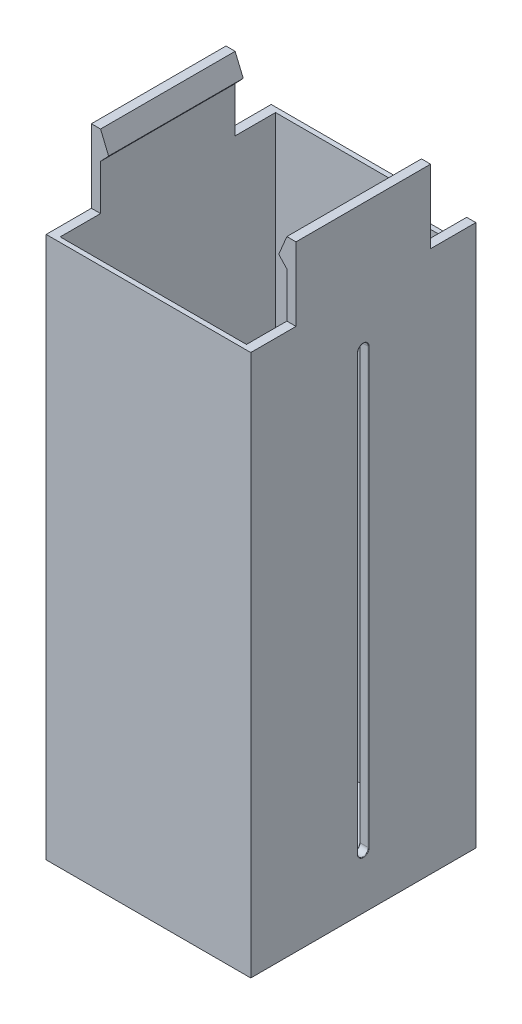
SolidWorks part; units mm, degrees
ref_plane "Front Plane" through (0, 0, 0) normal (0, 0, 1) x (1, 0, 0)
ref_plane "Top Plane" through (0, 0, 0) normal (0, 1, 0) x (1, 0, 0)
ref_plane "Right Plane" through (0, 0, 0) normal (1, 0, 0) x (0, 0, -1)
sketch "Sketch1" plane through (0, 0, 0) normal (0, 1, 0) x (1, 0, 0)
  line L0 (-19, 20.9) -> (42.3707, 20.9) construction
  line L1 (-19, 20.9) -> (19, 20.9)
  line L2 (-19, 20.9) -> (-19, -20.9)
  line L3 (-19, -20.9) -> (19, -20.9)
  line L4 (19, 20.9) -> (19, -20.9)
  line L5 (-19, 20.9) -> (19, -20.9) construction
  line L6 (-19, -20.9) -> (19, 20.9) construction
  line L7 (17.3, 20) -> (-17.3, 20)
  line L8 (17.3, 20) -> (17.3, -20)
  line L9 (17.3, -20) -> (-17.3, -20)
  line L10 (-17.3, 20) -> (-17.3, -20)
  line L11 (17.3, 20) -> (-17.3, -20) construction
  line L12 (17.3, -20) -> (-17.3, 20) construction
  point P0 (0, 0)
  point P6 (0, 0)
  dimension "D1" = 34.6
  dimension "D2" = 40
  dimension "D3" = 1.7
  dimension "D5" = 0.9
extrude "Boss-Extrude1" add sketch "Sketch1" along normal blind 100
sketch "Sketch2" plane through (0, 100, 0) normal (0, 1, 0) x (1, 0, 0)
  line L0 (-23.425, 0) -> (23.575, 0) construction
  line L1 (-19, 20.9) -> (-19, -20.9) construction
  line L3 (-17.3, 24.7662) -> (-17.3, -22.0296) construction
  line L4 (0, 23.9453) -> (0, -27.2839) construction
  line L5 (17.3, 12.5) -> (19, 12.5)
  line L6 (-17.3, -12.5) -> (-19, -12.5)
  line L7 (-17.3, -12.5) -> (-17.3, 12.5)
  line L8 (-17.3, 12.5) -> (-19, 12.5)
  line L9 (-19, -12.5) -> (-19, 12.5)
  line L10 (-17.3, -12.5) -> (-19, 12.5) construction
  line L11 (-17.3, 12.5) -> (-19, -12.5) construction
  line L12 (19, -12.5) -> (19, 12.5)
  line L13 (17.3, -12.5) -> (19, -12.5)
  line L14 (17.3, -12.5) -> (17.3, 12.5)
  line L15 (-17.3, 20) -> (-17.3, -20) construction
  point P11 (-18.15, 0)
  dimension "D2" = 25
  dimension "D3" = 20
extrude "Boss-Extrude2" add sketch "Sketch2" along normal blind 13.6
sketch "Sketch5" plane through (0, 0, 12.5) normal (0, 0, 1) x (1, 0, 0)
  line L0 (-15.8, 110) -> (15.8, 110) construction
  line L1 (17.3, 113.6) -> (17.3, 100) construction
  line L4 (-15.8, 110) -> (-17.3, 108.4)
  line L5 (-17.3, 108.4) -> (-17.3, 113.6)
  line L7 (-17.3, 113.6) -> (-15.8, 110)
  line L8 (17.3, 108.4) -> (17.3, 113.6)
  line L9 (15.8, 110) -> (17.3, 108.4)
  line L10 (17.3, 113.6) -> (15.8, 110)
  line L11 (-17.3, 113.6) -> (-17.3, 100) construction
  dimension "D1" = 10
  dimension "D2" = 1.6
  dimension "D3" = 1.5
  dimension "D4" = 1.6
  dimension "D5" = 1.5
extrude "Boss-Extrude5" add sketch "Sketch5" against normal up to surface (25 mm away) up to face at (18.15, 106.8, -12.5)
sketch "Sketch6" plane through (0, 0, 0) normal (0, -1, 0) x (1, 0, 0)
  line L0 (-19, 20.9) -> (19, 20.9) construction
  line L1 (19, 20.9) -> (-19, 20.9)
  line L2 (19, 20.9) -> (19, -20.9)
  line L3 (19, -20.9) -> (-19, -20.9)
  line L4 (-19, 20.9) -> (-19, -20.9)
extrude "Boss-Extrude6" add sketch "Sketch6" along normal blind 0.6
sketch "Sketch7" plane through (0, 0, -20.9) normal (0, 0, -1) x (-1, 0, 0)
  line L1 (-17.3, 100) -> (-4, 100)
  line L2 (-17.3, 100) -> (-17.3, 95.6)
  line L3 (-17.3, 95.6) -> (-4, 95.6)
  line L4 (-4, 100) -> (-4, 95.6)
  line L5 (-19, 100) -> (19, 100) construction
  line L6 (-19, 100) -> (-19, -0.6) construction
  dimension "D1" = 1.7
  dimension "D2" = 4.4
  dimension "D3" = 13.3
extrude "Cut-Extrude1" cut sketch "Sketch7" against normal blind 10
sketch "Sketch8" plane through (19, 0, 0) normal (1, 0, 0) x (0, 0, -1)
  line L0 (0, -0.6) -> (0, 113.6) construction
  line L1 (20.9, -0.6) -> (-20.9, -0.6) construction
  line L2 (-12.5, 113.6) -> (12.5, 113.6) construction
  line L3 (0, 9.4) -> (0, 90) construction
  line L4 (-1, 9.4) -> (-1, 90)
  line L5 (1, 9.4) -> (1, 90)
  line L6 (12.5, 100) -> (20.9, 100) construction
  arc A0 (-1, 9.4) -> (1, 9.4) centre (0, 9.4) ccw
  arc A1 (1, 90) -> (-1, 90) centre (0, 90) ccw
  point P8 (0, 49.7)
  dimension "D1" = 2
  dimension "D2" = 10
  dimension "D3" = 10
extrude "Cut-Extrude2" cut sketch "Sketch8" against normal blind 10
fillet "Fillet1" radius 0.1 8 edges at (17.3, 8.4, 0) (17.3, 49.7, -1) (17.3, 91, 0) (19, 91, 0) (19, 49.7, -1) (19, 8.4, 0) (17.3, 49.7, 1) (19, 49.7, 1)
